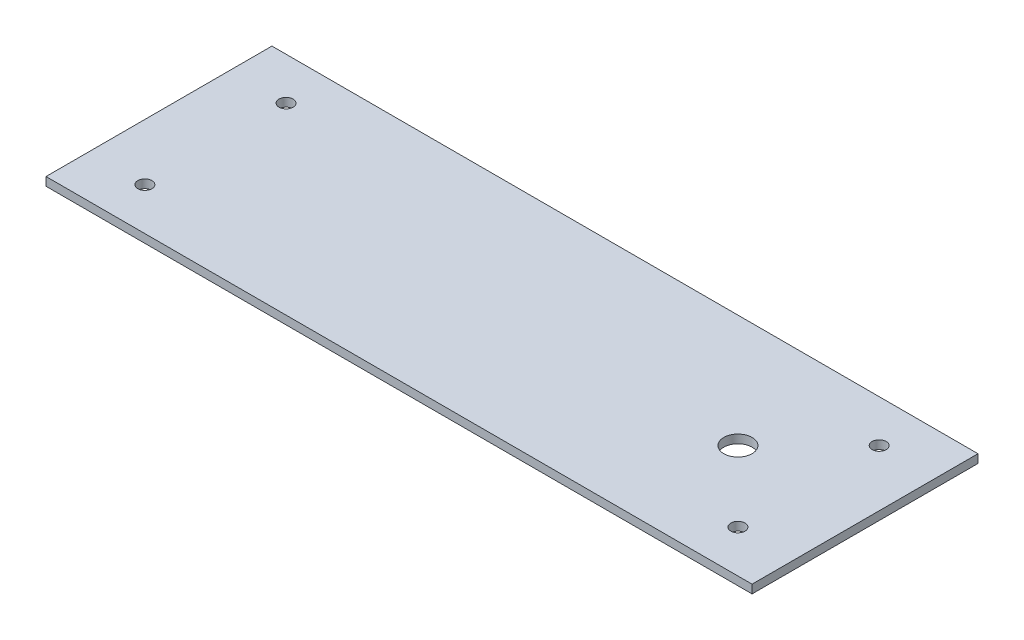
SolidWorks part; units mm, degrees
material "1060 Alloy"
ref_plane "Front Plane" through (0, 0, 0) normal (0, 0, 1) x (1, 0, 0)
ref_plane "Top Plane" through (0, 0, 0) normal (0, 1, 0) x (1, 0, 0)
ref_plane "Right Plane" through (0, 0, 0) normal (1, 0, 0) x (0, 0, -1)
sketch "Sketch1" plane through (0, 0, 0) normal (0, 1, 0) x (1, 0, 0)
  line L1 (-106.4783, 52.0745) -> (143.5217, 52.0745)
  line L2 (-106.4783, 52.0745) -> (-106.4783, -27.9255)
  line L3 (-106.4783, -27.9255) -> (143.5217, -27.9255)
  line L4 (143.5217, 52.0745) -> (143.5217, -27.9255)
  circle A0 centre (-86.4783, 37.0745) radius 2.5
  circle A1 centre (-86.4783, -12.9255) radius 2.5
  circle A2 centre (123.5217, 37.0745) radius 2.5
  circle A3 centre (123.5217, -12.9255) radius 2.5
  circle A4 centre (98.5217, 12.0745) radius 5
  dimension "D3" = 20
  dimension "D5" = 15
  dimension "D6" = 20
  dimension "D10" = 45
  dimension "D1" = 80
  dimension "D2" = 250
  dimension "D4" = 15
  dimension "D7" = 20
  dimension "D8" = 15
  dimension "D9" = 15
  dimension "D11" = 40
extrude "Boss-Extrude1" add sketch "Sketch1" along normal blind 3
